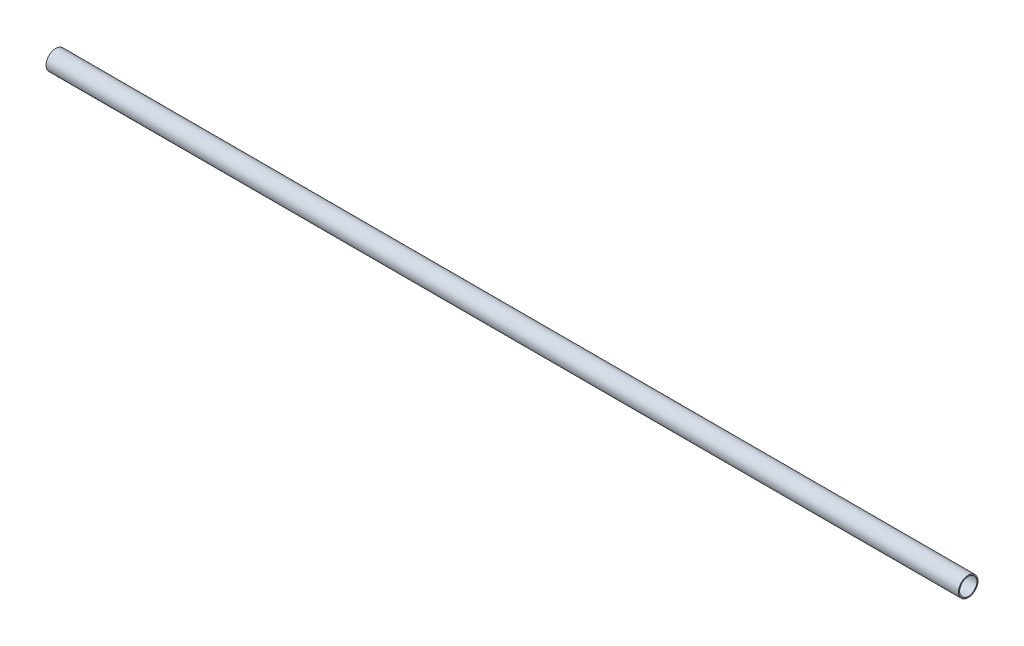
SolidWorks part; units mm, degrees
ref_plane "Front Plane" through (0, 0, 0) normal (0, 0, 1) x (1, 0, 0)
ref_plane "Top Plane" through (0, 0, 0) normal (0, 1, 0) x (1, 0, 0)
ref_plane "Right Plane" through (0, 0, 0) normal (1, 0, 0) x (0, 0, -1)
sketch "Sketch1" plane through (0, 0, 0) normal (1, 0, 0) x (0, 0, -1)
  circle A0 centre (0, 0) radius 1.5748
  circle A1 centre (0, 0) radius 1.397
extrude "Boss-Extrude1" add sketch "Sketch1" along normal blind 147.32
